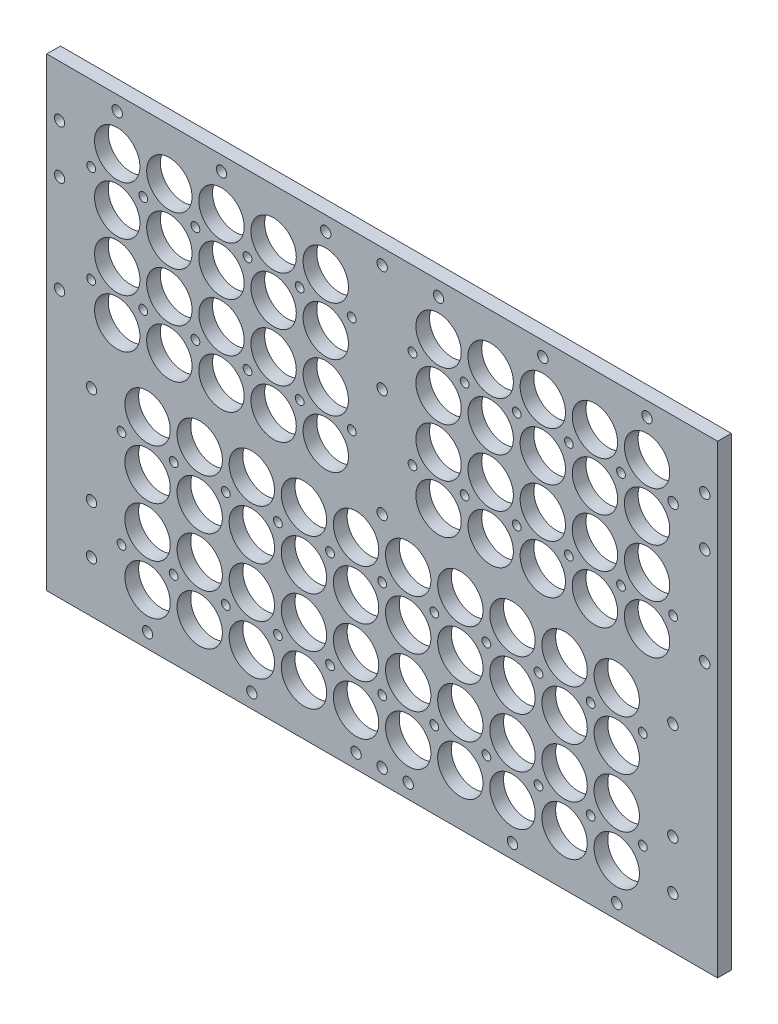
SolidWorks part; units mm, degrees
material "ABS"
ref_plane "X-Y Datum" through (0, 0, 0) normal (0, 0, 1) x (1, 0, 0)
ref_plane "X-Z Datum" through (0, 0, 0) normal (0, 1, 0) x (1, 0, 0)
ref_plane "Y-Z Datum" through (0, 0, 0) normal (1, 0, 0) x (0, 0, -1)
sketch "Sketch1" plane through (0, 0, 0) normal (0, 0, 1) x (1, 0, 0)
  line L0 (0, 79.7928) -> (0, 89.4448) construction
  line L1 (107.02, 69.2928) -> (110.15, 69.2928) construction
  line L2 (87.1747, 169.0657) -> (101.9042, 169.0657) construction
  line L3 (87.1747, 169.0657) -> (87.1747, 92.542) construction
  line L4 (87.1747, 92.542) -> (101.9042, 92.542) construction
  line L5 (101.9042, 169.0657) -> (101.9042, 92.542) construction
  line L6 (108.585, 69.2928) -> (108.585, 184.3906) construction
  line L7 (108.585, 126.8417) -> (102.235, 126.8417) construction
  line L8 (108.585, 126.8417) -> (114.935, 126.8417) construction
  line L9 (0, 89.4448) -> (101.9042, 89.4448) construction
  line L10 (82.4747, 89.435) -> (82.4747, 79.783) construction
  line L11 (91.8543, 92.542) -> (91.8543, 103.042) construction
  line L12 (91.8543, 103.042) -> (87.1747, 103.042) construction
  line L13 (-18.7453, 99.935) -> (-33.4747, 99.935) construction
  line L14 (0, -10.5) -> (0, -23.708) construction
  line L15 (231.2153, 178.2824) -> (231.2153, 191.4708) construction
  line L16 (241.7153, 167.7824) -> (254.9233, 167.7824) construction
  line L17 (0, 12.5976) -> (0, 10.5) construction
  line L18 (-46.6833, -23.708) -> (263.8533, -23.708)
  line L19 (-46.6833, -23.708) -> (-46.6833, 191.4708)
  line L20 (-46.6833, 191.4708) -> (263.8533, 191.4708)
  line L21 (263.8533, -23.708) -> (263.8533, 191.4708)
  line L22 (10.5, 23.0976) -> (13.63, 23.0976) construction
  line L23 (12.065, 23.0976) -> (12.065, 12.065) construction
  line L24 (-3.5453, 122.5508) -> (-0.4153, 122.5508) construction
  line L25 (-14.0453, 110.435) -> (-14.0453, 112.0508) construction
  line L26 (-1.9803, 122.5508) -> (-1.9803, 111.2478) construction
  line L27 (-4.7, 0) -> (-19.4295, 0) construction
  line L28 (-33.4747, 99.935) -> (-40.7447, 99.935) construction
  line L29 (48.26, -10.5) -> (48.26, -17.0302) construction
  line L30 (-14.0453, 111.2429) -> (-1.9803, 111.2429) construction
  line L31 (0, -10.5) -> (0, -17.0302) construction
  line L32 (-14.0453, 178.2824) -> (-14.0453, 184.7931) construction
  line L33 (182.9553, 89.435) -> (182.9553, 79.7928) construction
  line L34 (82.4747, 134.6666) -> (82.4747, 133.0508) construction
  line L35 (-19.4295, 0) -> (-25.9597, 0) construction
  line L36 (241.7153, 99.935) -> (269.6527, 99.935) construction
  line L37 (-43.9197, 167.753) -> (-43.9197, 180.2528) construction
  line L38 (-43.9197, 180.2528) -> (-46.6833, 180.2528) construction
  line L39 (261.0897, 167.753) -> (261.0897, 180.2528) construction
  line L40 (261.0897, 180.2528) -> (263.8533, 180.2528) construction
  circle A0 centre (0, 0) radius 10.5
  circle A1 centre (24.13, 0) radius 10.5
  circle A2 centre (0, 23.0976) radius 10.5
  circle A3 centre (24.13, 23.0976) radius 10.5
  circle A4 centre (0, 46.1952) radius 10.5
  circle A5 centre (24.13, 46.1952) radius 10.5
  circle A6 centre (0, 69.2928) radius 10.5
  circle A7 centre (24.13, 69.2928) radius 10.5
  circle A8 centre (48.26, 0) radius 10.5
  circle A9 centre (72.39, 0) radius 10.5
  circle A10 centre (96.52, 0) radius 10.5
  circle A11 centre (120.65, 0) radius 10.5
  circle A12 centre (144.78, 0) radius 10.5
  circle A13 centre (168.91, 0) radius 10.5
  circle A14 centre (193.04, 0) radius 10.5
  circle A15 centre (217.17, 0) radius 10.5
  circle A16 centre (48.26, 23.0976) radius 10.5
  circle A17 centre (72.39, 23.0976) radius 10.5
  circle A18 centre (96.52, 23.0976) radius 10.5
  circle A19 centre (120.65, 23.0976) radius 10.5
  circle A20 centre (144.78, 23.0976) radius 10.5
  circle A21 centre (168.91, 23.0976) radius 10.5
  circle A22 centre (193.04, 23.0976) radius 10.5
  circle A23 centre (217.17, 23.0976) radius 10.5
  circle A24 centre (48.26, 46.1952) radius 10.5
  circle A25 centre (72.39, 46.1952) radius 10.5
  circle A26 centre (96.52, 46.1952) radius 10.5
  circle A27 centre (120.65, 46.1952) radius 10.5
  circle A28 centre (144.78, 46.1952) radius 10.5
  circle A29 centre (168.91, 46.1952) radius 10.5
  circle A30 centre (193.04, 46.1952) radius 10.5
  circle A31 centre (217.17, 46.1952) radius 10.5
  circle A32 centre (48.26, 69.2928) radius 10.5
  circle A33 centre (72.39, 69.2928) radius 10.5
  circle A34 centre (96.52, 69.2928) radius 10.5
  circle A35 centre (120.65, 69.2928) radius 10.5
  circle A36 centre (144.78, 69.2928) radius 10.5
  circle A37 centre (168.91, 69.2928) radius 10.5
  circle A38 centre (193.04, 69.2928) radius 10.5
  circle A39 centre (217.17, 69.2928) radius 10.5
  circle A40 centre (82.4747, 99.935) radius 4.7 construction
  circle A41 centre (82.4747, 99.935) radius 10.5
  circle A42 centre (58.3447, 99.935) radius 10.5
  circle A43 centre (34.2147, 99.935) radius 10.5
  circle A44 centre (10.0847, 99.935) radius 10.5
  circle A45 centre (-14.0453, 99.935) radius 10.5
  circle A46 centre (58.3447, 122.5508) radius 10.5
  circle A47 centre (34.2147, 122.5508) radius 10.5
  circle A48 centre (10.0847, 122.5508) radius 10.5
  circle A49 centre (-14.0453, 122.5508) radius 10.5
  circle A50 centre (58.3447, 145.1666) radius 10.5
  circle A51 centre (34.2147, 145.1666) radius 10.5
  circle A52 centre (10.0847, 145.1666) radius 10.5
  circle A53 centre (-14.0453, 145.1666) radius 10.5
  circle A54 centre (58.3447, 167.7824) radius 10.5
  circle A55 centre (34.2147, 167.7824) radius 10.5
  circle A56 centre (10.0847, 167.7824) radius 10.5
  circle A57 centre (-14.0453, 167.7824) radius 10.5
  circle A58 centre (82.4747, 122.5508) radius 10.5
  circle A59 centre (82.4747, 145.1666) radius 10.5
  circle A60 centre (82.4747, 167.7824) radius 10.5
  circle A61 centre (231.2153, 99.935) radius 10.5
  circle A62 centre (207.0853, 99.935) radius 10.5
  circle A63 centre (182.9553, 99.935) radius 10.5
  circle A64 centre (182.9553, 122.5508) radius 10.5
  circle A65 centre (207.0853, 122.5508) radius 10.5
  circle A66 centre (231.2153, 122.5508) radius 10.5
  circle A67 centre (231.2153, 145.1666) radius 10.5
  circle A68 centre (231.2153, 167.7824) radius 10.5
  circle A69 centre (207.0853, 167.7824) radius 10.5
  circle A70 centre (207.0853, 145.1666) radius 10.5
  circle A71 centre (182.9553, 145.1666) radius 10.5
  circle A72 centre (182.9553, 167.7824) radius 10.5
  circle A73 centre (158.8253, 167.7824) radius 10.5
  circle A74 centre (158.8253, 145.1666) radius 10.5
  circle A75 centre (158.8253, 122.5508) radius 10.5
  circle A76 centre (158.8253, 99.935) radius 10.5
  circle A77 centre (134.6953, 99.935) radius 10.5
  circle A78 centre (134.6953, 122.5508) radius 10.5
  circle A79 centre (134.6953, 145.1666) radius 10.5
  circle A80 centre (134.6953, 167.7824) radius 10.5
  circle A81 centre (12.065, 12.065) radius 2.032
  circle A82 centre (36.195, 12.065) radius 2.032
  circle A83 centre (60.325, 12.065) radius 2.032
  circle A84 centre (84.455, 12.065) radius 2.032
  circle A85 centre (108.585, 12.065) radius 2.032
  circle A86 centre (132.715, 12.065) radius 2.032
  circle A87 centre (156.845, 12.065) radius 2.032
  circle A88 centre (180.975, 12.065) radius 2.032
  circle A89 centre (205.105, 12.065) radius 2.032
  circle A90 centre (229.235, 12.065) radius 2.032
  circle A91 centre (36.195, 57.277) radius 2.032
  circle A92 centre (60.325, 57.277) radius 2.032
  circle A93 centre (84.455, 57.277) radius 2.032
  circle A94 centre (108.585, 57.277) radius 2.032
  circle A95 centre (132.715, 57.277) radius 2.032
  circle A96 centre (156.845, 57.277) radius 2.032
  circle A97 centre (180.975, 57.277) radius 2.032
  circle A98 centre (205.105, 57.277) radius 2.032
  circle A99 centre (229.235, 57.277) radius 2.032
  circle A100 centre (12.065, 57.277) radius 2.032
  circle A101 centre (-12.065, 57.277) radius 2.032
  circle A102 centre (-12.065, 12.065) radius 2.032
  circle A103 centre (-1.9803, 111.2478) radius 2.032
  circle A104 centre (22.1497, 111.2478) radius 2.032
  circle A105 centre (46.2797, 111.2478) radius 2.032
  circle A106 centre (70.4097, 111.2478) radius 2.032
  circle A107 centre (94.5397, 111.2478) radius 2.032
  circle A108 centre (22.1497, 156.4598) radius 2.032
  circle A109 centre (46.2797, 156.4598) radius 2.032
  circle A110 centre (70.4097, 156.4598) radius 2.032
  circle A111 centre (94.5397, 156.4598) radius 2.032
  circle A112 centre (-1.9803, 156.4598) radius 2.032
  circle A113 centre (-26.1103, 111.2478) radius 2.032
  circle A114 centre (-26.1103, 156.4598) radius 2.032
  circle A115 centre (122.6303, 156.4598) radius 2.032
  circle A116 centre (122.6303, 111.2478) radius 2.032
  circle A117 centre (146.7603, 111.2478) radius 2.032
  circle A118 centre (146.7603, 156.4598) radius 2.032
  circle A119 centre (170.8903, 156.4598) radius 2.032
  circle A120 centre (170.8903, 111.2478) radius 2.032
  circle A121 centre (195.0203, 111.2478) radius 2.032
  circle A122 centre (195.0203, 156.4598) radius 2.032
  circle A123 centre (219.1503, 156.4598) radius 2.032
  circle A124 centre (219.1503, 111.2478) radius 2.032
  circle A125 centre (243.2803, 111.2478) radius 2.032
  circle A126 centre (243.2803, 156.4598) radius 2.032
  circle A128 centre (-40.7447, 99.935) radius 1.4713
  circle A132 centre (-25.9597, 0) radius 0.466
  circle A133 centre (0, 0) radius 4.7 construction
  circle A134 centre (-25.9597, 22.606) radius 0.466
  circle A136 centre (-25.9597, 67.818) radius 0.466
  circle A137 centre (-25.9597, 45.212) radius 0.466 [skipped]
  circle A138 centre (-40.7447, 122.541) radius 1.4713 [skipped]
  circle A139 centre (-40.7447, 145.147) radius 1.4713
  circle A140 centre (-40.7447, 167.753) radius 1.4713
  circle A141 centre (0, -17.0302) radius 1.1227
  circle A142 centre (24.13, -17.0302) radius 1.1227 [skipped]
  circle A143 centre (48.26, -17.0302) radius 1.1227
  circle A144 centre (72.39, -17.0302) radius 1.1227 [skipped]
  circle A145 centre (96.52, -17.0302) radius 1.1227
  circle A146 centre (120.65, -17.0302) radius 1.1227
  circle A147 centre (144.78, -17.0302) radius 1.1227 [skipped]
  circle A148 centre (168.91, -17.0302) radius 1.1227
  circle A149 centre (193.04, -17.0302) radius 1.1227 [skipped]
  circle A150 centre (217.17, -17.0302) radius 1.1227
  circle A151 centre (257.9147, 167.753) radius 1.4713
  circle A152 centre (257.9147, 145.147) radius 1.4713
  circle A153 centre (257.9147, 99.935) radius 1.4713
  circle A154 centre (243.1297, 67.818) radius 0.466
  circle A155 centre (243.1297, 22.606) radius 0.466
  circle A156 centre (243.1297, 0) radius 0.466
  circle A157 centre (-14.0453, 184.7931) radius 2.232
  circle A158 centre (10.0847, 184.7931) radius 2.232 [skipped]
  circle A159 centre (34.2147, 184.7931) radius 2.232
  circle A160 centre (58.3447, 184.7931) radius 2.232 [skipped]
  circle A161 centre (82.4747, 184.7931) radius 2.232
  circle A162 centre (134.6953, 184.7931) radius 2.232
  circle A163 centre (182.9553, 184.7931) radius 2.232
  circle A164 centre (231.2153, 184.7931) radius 2.232
  circle A166 centre (108.585, 184.3906) radius 1.6159
  circle A167 centre (108.585, 134.6568) radius 0.9583
  circle A168 centre (108.585, 84.6188) radius 1.565
  circle A169 centre (108.585, -17.0302) radius 1.565
  circle A170 centre (-14.0453, 99.935) radius 4.7 construction
  circle A171 centre (-40.7447, 167.753) radius 3.175 construction
  dimension "D1" = 10
  dimension "D3" = 9.652
  dimension "D4" = 10.5
  dimension "D7" = 10
  dimension "D10" = 5
  dimension "D13" = 4
  dimension "D17" = 14.7295
  dimension "D20" = 9.4
  dimension "D5" = 5
  dimension "D14" = 4
  dimension "D15" = 10
  dimension "D16" = 5
  dimension "D18" = 7.27
  dimension "D19" = 14.7295
  dimension "D21" = 6.5302
  dimension "D2" = 4
  dimension "D6" = 4
  dimension "D8" = 2
  dimension "D9" = 2
  dimension "D11" = 2
  dimension "D12" = 2
extrude "Boss-Extrude1" add sketch "Sketch1" along normal blind 6.35
hole_wizard "M4 Clearance Hole1" positions "Sketch2" profile "Sketch3" hole size "M4" standard "ANSI Metric" end condition through all
sketch "Sketch2" plane through (0, 0, 6.35) normal (0, 0, 1) x (1, 0, 0)
  point P0 (0, -17.0302)
  point P3 (-25.9597, 0)
  point P6 (-25.9597, 22.606)
  point P9 (-25.9597, 67.818)
  point P12 (-40.7447, 99.935)
  point P15 (-40.7447, 145.147)
  point P18 (-40.7447, 167.753)
  point P21 (-14.0453, 184.7931)
  point P24 (34.2147, 184.7931)
  point P27 (82.4747, 184.7931)
  point P30 (108.585, 184.3906)
  point P33 (134.6953, 184.7931)
  point P36 (182.9553, 184.7931)
  point P39 (231.2153, 184.7931)
  point P42 (257.9147, 167.753)
  point P45 (243.2803, 156.4598)
  point P48 (257.9147, 145.147)
  point P51 (257.9147, 99.935)
  point P54 (243.1297, 67.818)
  point P57 (243.1297, 22.606)
  point P60 (243.1297, 0)
  point P63 (217.17, -17.0302)
  point P66 (168.91, -17.0302)
  point P69 (120.65, -17.0302)
  point P72 (108.585, -17.0302)
  point P75 (96.52, -17.0302)
  point P78 (48.26, -17.0302)
  point P81 (108.585, 84.6188)
  point P92 (108.585, 134.6568)
sketch "Sketch3" plane through (0, -17.0302, 6.35) normal (1, 0, 0) x (0, -1, 0)
  line L0 (0, 0) -> (0, 6.35)
  line L1 (0, 6.35) -> (2.4, 6.35)
  line L2 (2.4, 6.35) -> (2.4, 0)
  line L5 (2.4, 0) -> (0, 0)
  line L11 (0, -6.35) -> (0, 107.95) construction
  dimension "Thru Hole Dia." = 4.8
  dimension "Thru Hole Depth" = 6.35
